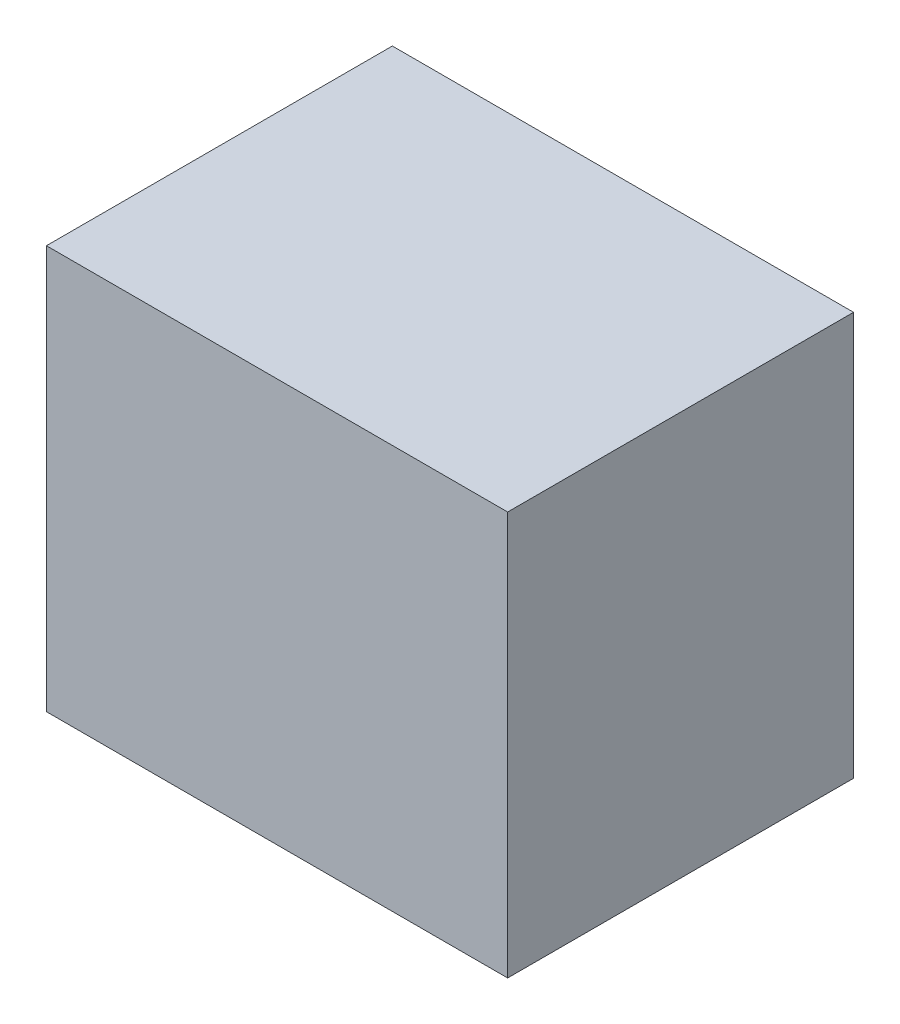
SolidWorks part; units mm, degrees
material "Titanium Ti-8Mn, Annealed"
ref_plane "Front Plane" through (0, 0, 0) normal (0, 0, 1) x (1, 0, 0)
ref_plane "Top Plane" through (0, 0, 0) normal (0, 1, 0) x (1, 0, 0)
ref_plane "Right Plane" through (0, 0, 0) normal (1, 0, 0) x (0, 0, -1)
sketch "Sketch1" plane through (0, 0, 0) normal (0, 0, 1) x (1, 0, 0)
  line L1 (0, 0) -> (800, 0)
  line L2 (0, 0) -> (0, 700)
  line L3 (0, 700) -> (800, 700)
  line L4 (800, 0) -> (800, 700)
  dimension "D1" = 800
  dimension "D2" = 700
extrude "Boss-Extrude1" add sketch "Sketch1" along normal blind 600
